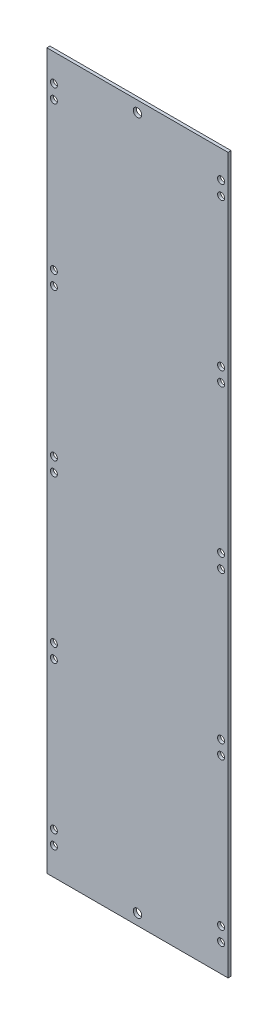
SolidWorks part; units mm, degrees
ref_plane "Front Plane" through (0, 0, 0) normal (0, 0, 1) x (1, 0, 0)
ref_plane "Top Plane" through (0, 0, 0) normal (0, 1, 0) x (1, 0, 0)
ref_plane "Right Plane" through (0, 0, 0) normal (1, 0, 0) x (0, 0, -1)
sketch "Sketch1" plane through (0, 0, 0) normal (0, 0, 1) x (1, 0, 0)
  line L1 (0, 0) -> (83, 0)
  line L2 (0, 0) -> (0, 327.5)
  line L3 (0, 327.5) -> (83, 327.5)
  line L4 (83, 0) -> (83, 327.5)
  dimension "D1" = 83
  dimension "D2" = 327.5
extrude "Boss-Extrude1" add sketch "Sketch1" along normal blind 1.397
sketch "Sketch2" plane through (0, 0, 1.397) normal (0, 0, 1) x (1, 0, 0)
  line L0 (0, 327.5) -> (0, 0) construction
  line L1 (83, 327.5) -> (0, 327.5) construction
  line L2 (0, 0) -> (83, 0) construction
  circle A0 centre (3.2, 314.9) radius 1.6
  circle A1 centre (3.2, 308.5) radius 1.6
  circle A2 centre (79.8, 314.9) radius 1.6
  circle A3 centre (79.8, 308.5) radius 1.6
  circle A4 centre (3.2, 240.925) radius 1.6
  circle A5 centre (3.2, 234.525) radius 1.6
  circle A6 centre (79.8, 240.925) radius 1.6
  circle A7 centre (79.8, 234.525) radius 1.6
  circle A8 centre (3.2, 166.95) radius 1.6
  circle A9 centre (3.2, 160.55) radius 1.6
  circle A10 centre (79.8, 166.95) radius 1.6
  circle A11 centre (79.8, 160.55) radius 1.6
  circle A12 centre (3.2, 92.975) radius 1.6
  circle A13 centre (3.2, 86.575) radius 1.6
  circle A14 centre (79.8, 92.975) radius 1.6
  circle A15 centre (79.8, 86.575) radius 1.6
  circle A16 centre (3.2, 19) radius 1.6
  circle A17 centre (3.2, 12.6) radius 1.6
  circle A18 centre (79.8, 19) radius 1.6
  circle A19 centre (79.8, 12.6) radius 1.6
  dimension "D1" = 3.2
  dimension "D4" = 3.2
  dimension "D2" = 3.2
  dimension "D3" = 12.6
  dimension "D5" = 6.4
  dimension "D6" = 3.2
  dimension "D9" = 12.6
  dimension "D7" = 2
  dimension "D8" = 5
extrude "Cut-Extrude1" cut sketch "Sketch2" against normal blind 1.397
sketch "Sketch3" plane through (0, 0, 1.397) normal (0, 0, 1) x (1, 0, 0)
  line L0 (83, 327.5) -> (0, 327.5) construction
  line L1 (0, 327.5) -> (0, 0) construction
  line L2 (83, 0) -> (83, 327.5) construction
  line L3 (0, 0) -> (83, 0) construction
  circle A0 centre (41.5, 322.524) radius 1.93
  circle A1 centre (41.5, 4.976) radius 1.93
  dimension "D1" = 3.86
  dimension "D5" = 3.86
  dimension "D2" = 4.976
  dimension "D3" = 41.5
  dimension "D4" = 41.5
  dimension "D6" = 41.5
  dimension "D7" = 41.5
  dimension "D8" = 4.976
extrude "Cut-Extrude2" cut sketch "Sketch3" against normal blind 1.397
